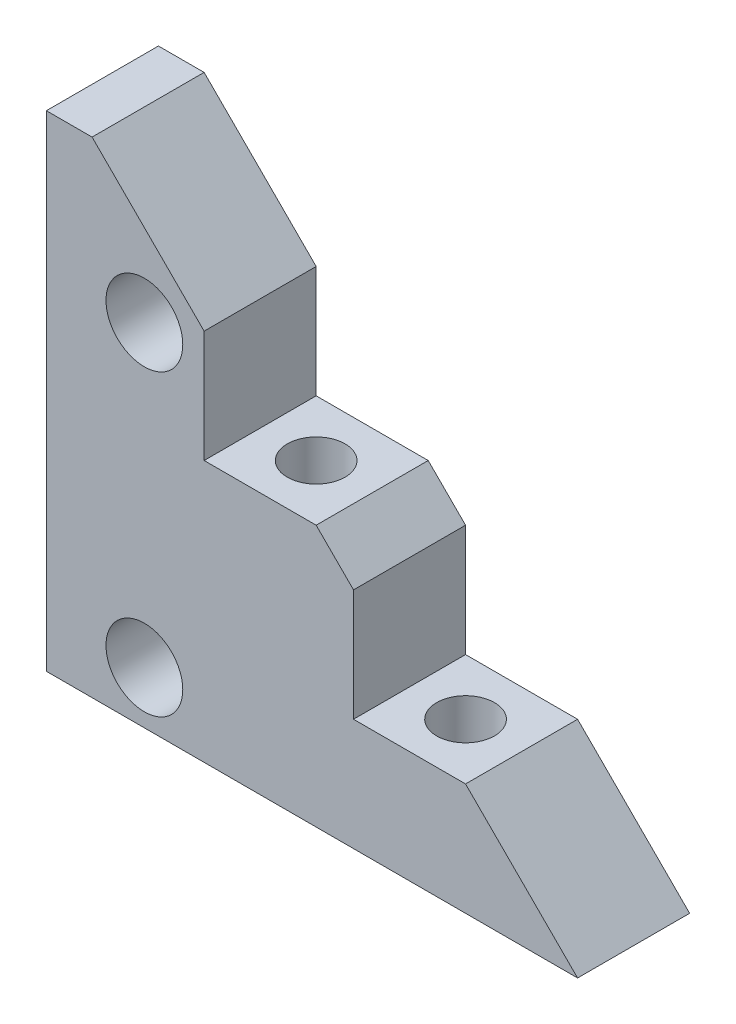
SolidWorks part; units mm, degrees
material "6061 Alloy"
ref_plane "Front Plane" through (0, 0, 0) normal (0, 0, 1) x (1, 0, 0)
ref_plane "Top Plane" through (0, 0, 0) normal (0, 1, 0) x (1, 0, 0)
ref_plane "Right Plane" through (0, 0, 0) normal (1, 0, 0) x (0, 0, -1)
sketch "Sketch2" plane through (0, 0, 0) normal (0, 0, 1) x (1, 0, 0)
  line L0 (0, 0) -> (41.275, 0)
  line L1 (41.275, 0) -> (31.75, 9.525)
  line L2 (0, 41.275) -> (0, 0)
  line L3 (9.525, 31.75) -> (9.525, 22.225)
  line L4 (9.525, 22.225) -> (19.05, 22.225)
  line L5 (22.225, 19.05) -> (22.225, 9.525)
  line L6 (22.225, 9.525) -> (31.75, 9.525)
  line L7 (9.525, 31.75) -> (0, 41.275)
  line L8 (22.225, 19.05) -> (19.05, 22.225)
  point P9 (8.7282, 20.2609)
  point P11 (9.525, 20.659)
  dimension "D1" = 41.275
  dimension "D2" = 9.525
  dimension "D3" = 3.175
  dimension "D4" = 9.525
extrude "Boss-Extrude1" add sketch "Sketch2" along normal blind 9.525
sketch "Sketch3" plane through (0, 0, 9.525) normal (0, 0, 1) x (1, 0, 0)
  line L0 (0, 41.275) -> (0, 0) construction
  circle A0 centre (4.445, 29.845) radius 3.2639
  circle A1 centre (4.445, 4.445) radius 3.2639
  point P4 (4.2494, 5.51)
  point P7 (4.445, 4.6944)
  dimension "D1" = 6.5278
  dimension "D2" = 25.4
  dimension "D3" = 4.445
  dimension "D4" = 4.445
extrude "Cut-Extrude1" cut sketch "Sketch3" against normal through all
sketch "Sketch4" plane through (0, 0, 0) normal (0, 0, -1) x (-1, 0, 0)
  line L1 (0, 41.275) -> (3.8862, 41.275)
  line L2 (0, 41.275) -> (0, 0)
  line L3 (0, 0) -> (3.8862, 0)
  line L4 (3.8862, 41.275) -> (3.8862, 0)
  point P4 (0, 0)
  point P5 (3.8862, 0)
  dimension "D1" = 3.8862
extrude "Boss-Extrude2" add sketch "Sketch4" against normal up to surface (9.525 mm away) up to face at (7.7089, 29.845, 9.525)
hole_wizard "#10 (0.1935) Diameter Hole1" positions "Sketch5" profile "Sketch6" hole size "#10" standard "ANSI Inch" end condition through all
sketch "Sketch5" plane through (0, 22.225, 0) normal (0, 1, 0) x (1, 0, 0)
  line L0 (9.525, -9.525) -> (9.525, 0) construction
  line L1 (22.225, -9.525) -> (22.225, 0) construction
  point P0 (14.2875, -4.7625)
  point P2 (26.9875, -4.7625)
  point P5 (27.3138, -4.7625)
  dimension "D1" = 4.7625
  dimension "D2" = 4.7625
  dimension "D3" = 4.7625
sketch "Sketch6" plane through (14.2875, 22.225, 4.7625) normal (1, 0, 0) x (0, 0, 1)
  line L0 (0, 0) -> (0, 22.225)
  line L1 (0, 22.225) -> (2.4574, 22.225)
  line L2 (2.4574, 22.225) -> (2.4574, 0)
  line L5 (2.4574, 0) -> (0, 0)
  line L11 (0, -6.35) -> (0, 107.95) construction
  dimension "Thru Hole Dia." = 4.9149
  dimension "Thru Hole Depth" = 22.225
